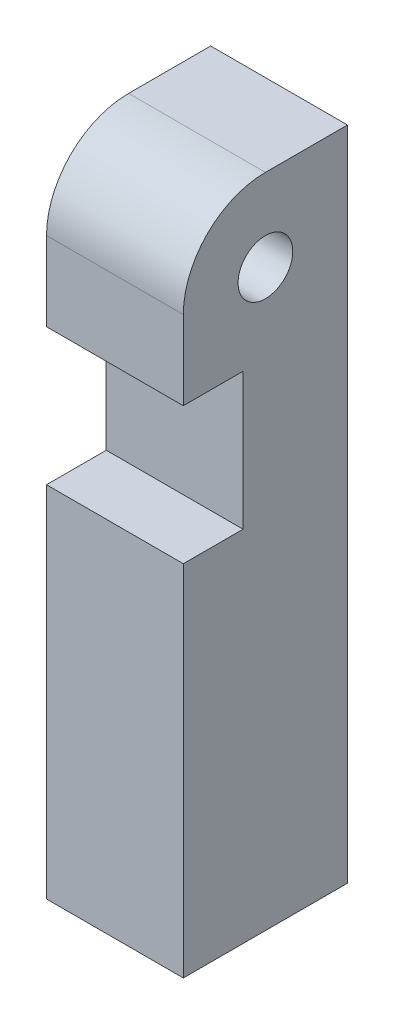
SolidWorks part; units mm, degrees
ref_plane "Front Plane" through (0, 0, 0) normal (0, 0, 1) x (1, 0, 0)
ref_plane "Top Plane" through (0, 0, 0) normal (0, 1, 0) x (1, 0, 0)
ref_plane "Right Plane" through (0, 0, 0) normal (1, 0, 0) x (0, 0, -1)
sketch "Elevator Paddle" plane through (0, 0, 0) normal (1, 0, 0) x (0, 0, -1)
  line L0 (3.81, 3.81) -> (3.81, -26.67)
  line L1 (3.81, -26.67) -> (-3.81, -26.67)
  line L2 (-3.81, -26.67) -> (-3.81, -10.016)
  line L3 (-6.4983, 38.1) -> (3.6147, 38.1)
  line L4 (3.81, 3.81) -> (0, 3.81)
  line L5 (-3.81, -3.666) -> (-1.0375, -3.666)
  line L6 (-1.0375, -3.666) -> (-1.0375, -10.016)
  line L7 (-1.0375, -10.016) -> (-3.81, -10.016)
  line L8 (-3.81, -3.666) -> (-3.81, 0)
  line L9 (1.735, 3.81) -> (1.735, -26.67) construction
  line L10 (-3.81, -12.8389) -> (1.735, -12.8389) construction
  line L11 (-1.0375, -10.016) -> (-1.0375, -12.8389) construction
  circle A0 centre (0, 0) radius 1.27
  arc A1 (0, 3.81) -> (-3.81, 0) centre (0, 0) ccw
  point P17 (-1.0375, -12.8389)
  dimension "D3" = 2.54
  dimension "D1" = 2.54
  dimension "D2" = 2.54
  dimension "D4" = 25.4
  dimension "D6" = 2.7725
  dimension "D7" = 2.54
  dimension "D5" = 6.35
  dimension "D8" = 2.075
extrude "Boss-Extrude1" add sketch "Elevator Paddle" along normal blind 6.35
equation "\"Ball Diameter\"= 1.75in"
equation "\"Sheet Thickness\"= 0.25in"
equation "\"Screw Diameter\"= .17in"
equation "\"Robot Diameter\"= 14in"
equation "\"Castor Screw Diameter\"= 0.22in"
equation "\"Wheel Diameter\" = 4in"
equation "\"Nut Diameter\" = 8.4mm"
equation "\"Nut Height\" = 2.9mm"
equation "\"Screw Height\" = 0.55in"
equation "\"D1@Boss-Extrude1\"=\"Sheet Thickness\""
equation "\"Pulley Diameter\" = 1in"
equation "\"Reactor Height\" = 14in"
equation "\"Elevator Height\" = 11.5in"
equation "\"Elevator Width\" = \"Ball Diameter\" + 0.25in"
equation "\"Elevator Bearing Diameter\" = sqr(2*(\"Sheet Thickness\"^2)) + 0.2in"
equation "\"Elevator Axle Endcap Diameter\" = \"Pulley Diameter\" + 0.25in"
equation "\"Elevator Axle Length\" = \"Elevator Width\" + 8*\"Sheet Thickness\""
equation "\"Elevator Clearance from Axis\" = 3.28in"
equation "\"D5@Elevator Paddle\"=\"Sheet Thickness\""
equation "\"D6@Elevator Paddle\"=\"Sheet Thickness\"/2"
equation "\"D8@Elevator Paddle\"=(\"Elevator Axle Endcap Diameter\"-\"Pulley Diameter\")/2 - 1.1mm"
